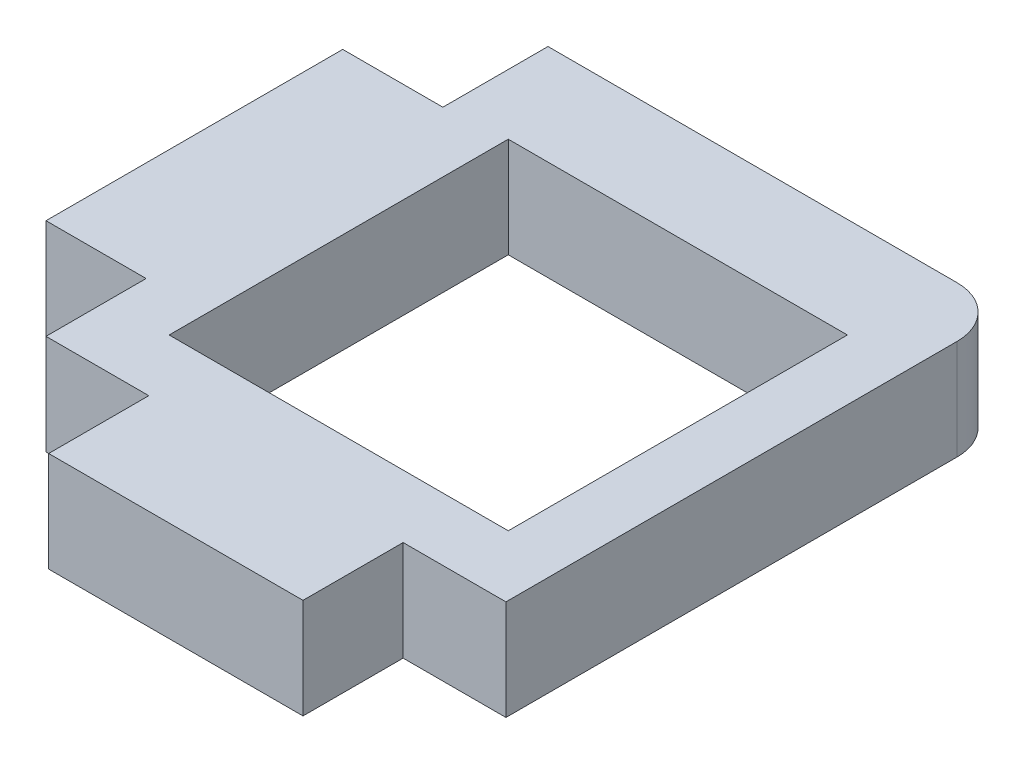
SolidWorks part; units mm, degrees
ref_plane "Front Plane" through (0, 0, 0) normal (0, 0, 1) x (1, 0, 0)
ref_plane "Top Plane" through (0, 0, 0) normal (0, 1, 0) x (1, 0, 0)
ref_plane "Right Plane" through (0, 0, 0) normal (1, 0, 0) x (0, 0, -1)
sketch "스케치1" plane through (0, 0, 0) normal (0, 1, 0) x (1, 0, 0)
  line L0 (0, 0.9398) -> (0, 0)
  line L1 (6.8897, -6.0198) -> (-6.8897, -6.0198) construction
  line L2 (6.8897, -6.0198) -> (6.8897, 6.0198)
  line L3 (6.8897, 6.0198) -> (-6.8898, 6.0198) construction
  line L4 (-6.8897, -6.0198) -> (-6.8898, 6.0198) construction
  line L5 (6.8897, -6.0198) -> (-6.8898, 6.0198) construction
  line L6 (6.8897, 6.0198) -> (-6.8897, -6.0198) construction
  line L7 (-5.08, -4.1402) -> (5.08, -4.1402)
  line L8 (-5.08, -4.1402) -> (-5.08, 6.0198)
  line L9 (-5.08, 6.0198) -> (5.08, 6.0198)
  line L10 (5.08, -4.1402) -> (5.08, 6.0198)
  line L11 (-5.08, -4.1402) -> (5.08, 6.0198) construction
  line L12 (-5.08, 6.0198) -> (5.08, -4.1402) construction
  line L13 (5.08, -4.1402) -> (6.8897, -4.1402) construction
  line L14 (-5.08, 6.0198) -> (5.08, 6.0198)
  line L15 (-5.08, 6.0198) -> (-5.08, 9.0198) construction
  line L16 (-5.08, 9.0198) -> (5.08, 9.0198)
  line L17 (5.08, 6.0198) -> (5.08, 9.0198) construction
  line L18 (-5.08, 6.0198) -> (5.08, 9.0198) construction
  line L19 (-5.08, 9.0198) -> (5.08, 6.0198) construction
  line L20 (6.8897, 6.0198) -> (6.8897, 7.4958)
  line L21 (5.3657, 9.0198) -> (5.08, 9.0198)
  line L22 (-5.08, 9.0198) -> (-6.8898, 9.0198)
  line L23 (-6.8898, 9.0198) -> (-6.8898, 6.0198) construction
  line L24 (0, 0) -> (0, -7.5198) construction
  line L25 (-3.81, -9.0198) -> (3.81, -9.0198)
  line L26 (-3.81, -9.0198) -> (-3.81, -6.0198)
  line L27 (-3.81, -6.0198) -> (3.81, -6.0198) construction
  line L28 (3.81, -9.0198) -> (3.81, -6.0198)
  line L29 (-3.81, -9.0198) -> (3.81, -6.0198) construction
  line L30 (-3.81, -6.0198) -> (3.81, -9.0198) construction
  line L31 (-9.8897, -3.0198) -> (-6.8897, -3.0198)
  line L32 (-9.8897, -3.0198) -> (-9.8897, 5.8702)
  line L33 (-9.8897, 5.8702) -> (-6.8897, 5.8702)
  line L34 (-6.8897, -3.0198) -> (-6.8897, 5.8702) construction
  line L35 (-9.8897, -3.0198) -> (-6.8897, 5.8702) construction
  line L36 (-9.8897, 5.8702) -> (-6.8897, -3.0198) construction
  line L37 (-6.8898, 9.0198) -> (-6.8897, -6.0198) construction
  line L38 (-6.8897, 1.4252) -> (-8.3898, 1.4252) construction
  line L39 (-6.8897, -3.0198) -> (-6.8897, -6.0198)
  line L40 (-6.8897, 5.8702) -> (-6.8898, 9.0198)
  line L41 (-6.8897, -6.0198) -> (-3.81, -6.0198)
  line L42 (3.81, -6.0198) -> (6.8897, -6.0198)
  arc A0 (6.8897, 7.4958) -> (5.3657, 9.0198) centre (5.3657, 7.4958) ccw
  point P0 (0, 0)
  point P5 (0, 0.9398)
  point P16 (0, 7.5198)
  point P17 (0, -7.5198)
  point P25 (-8.3897, 1.4252)
  dimension "D12" = 1.524
  dimension "D1" = 12.0396
  dimension "D2" = 13.7795
  dimension "D3" = 10.16
  dimension "D4" = 10.16
  dimension "D5" = 1.8097
  dimension "D6" = 3
  dimension "D7" = 7.62
  dimension "D8" = 3
  dimension "D9" = 8.89
  dimension "D10" = 3
  dimension "D11" = 3
extrude "보스-돌출1" add sketch "스케치1" against normal blind 3 contours L20 A0 L21 L16 L22 L40 L33 L32 L31 L39 L41 L26 L25 L28 L42 L2 L10 L7 L8 L9
